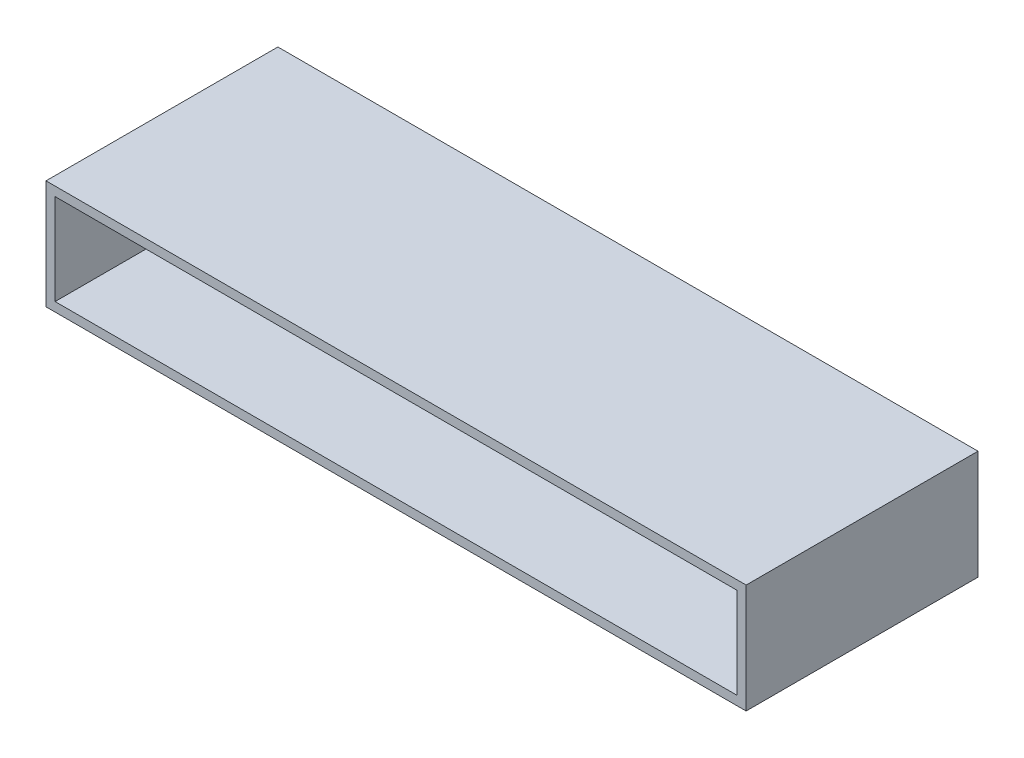
SolidWorks part; units mm, degrees
ref_plane "Front Plane" through (0, 0, 0) normal (0, 0, 1) x (1, 0, 0)
ref_plane "Top Plane" through (0, 0, 0) normal (0, 1, 0) x (1, 0, 0)
ref_plane "Right Plane" through (0, 0, 0) normal (1, 0, 0) x (0, 0, -1)
sketch "Sketch1" plane through (0, 0, 0) normal (0, 0, 1) x (1, 0, 0)
  line L1 (0, 0) -> (154, 0)
  line L2 (0, 0) -> (0, 24)
  line L3 (0, 24) -> (154, 24)
  line L4 (154, 0) -> (154, 24)
  line L6 (2, 2) -> (152, 2)
  line L7 (2, 2) -> (2, 22)
  line L8 (2, 22) -> (152, 22)
  line L9 (152, 2) -> (152, 22)
  dimension "D1" = 2
  dimension "D2" = 152
  dimension "D3" = 154
  dimension "D4" = 2
  dimension "D5" = 22
  dimension "D6" = 24
extrude "Profile" add sketch "Sketch1" along normal blind 51
sketch "Sketch2" plane through (0, 0, 0) normal (0, 0, 1) x (1, 0, 0)
  line L1 (2, 2) -> (152, 2)
  line L2 (2, 2) -> (2, 22)
  line L3 (2, 22) -> (152, 22)
  line L4 (152, 2) -> (152, 22)
  dimension "D1" = 150
  dimension "D2" = 20
extrude "Back" add sketch "Sketch2" along normal blind 2
equation "\"Profile_Depth\"= 51mm"
equation "\"D1@Profile\" = \"Profile_Depth\""
equation "\"Profile_Sketch_1\"= 2mm"
equation "\"D1@Sketch1\" = \"Profile_Sketch_1\""
equation "\"Profile_Sketch_2\"= 152mm"
equation "\"D2@Sketch1\" = \"Profile_Sketch_2\""
equation "\"Profile_Sketch_3\"= 154mm"
equation "\"D3@Sketch1\" = \"Profile_Sketch_3\""
equation "\"Profile_Sketch_4\"= 2mm"
equation "\"D4@Sketch1\" = \"Profile_Sketch_4\""
equation "\"Profile_Sketch_5\"= 22mm"
equation "\"D5@Sketch1\" = \"Profile_Sketch_5\""
equation "\"Profile_Sketch_6\"= 24mm"
equation "\"D6@Sketch1\" = \"Profile_Sketch_6\""
equation "\"Back_Depth\"= 2mm"
equation "\"D1@Back\" = \"Back_Depth\""
equation "\"Back_Sketch_1\"= 150mm"
equation "\"D1@Sketch2\" = \"Back_Sketch_1\""
equation "\"Back_Sketch_2\"= 20mm"
equation "\"D2@Sketch2\" = \"Back_Sketch_2\""
equation "\"EnvelopeWidth\"= 154mm"
equation "\"EnvelopeHeight\"= 24mm"
